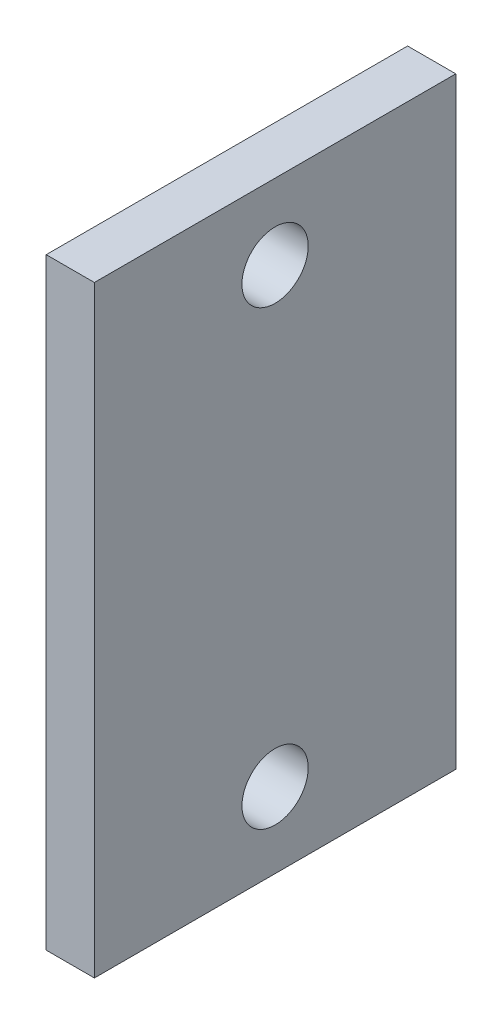
SolidWorks part; units mm, degrees
ref_plane "Front Plane" through (0, 0, 0) normal (0, 0, 1) x (1, 0, 0)
ref_plane "Top Plane" through (0, 0, 0) normal (0, 1, 0) x (1, 0, 0)
ref_plane "Right Plane" through (0, 0, 0) normal (1, 0, 0) x (0, 0, -1)
other "Configuration Table"
sketch "Sketch1" plane through (0, 0, 0) normal (1, 0, 0) x (0, 0, -1)
  line L1 (-6, -10) -> (6, -10)
  line L2 (-6, -10) -> (-6, 10)
  line L3 (-6, 10) -> (6, 10)
  line L4 (6, -10) -> (6, 10)
  line L5 (-6, -10) -> (6, 10) construction
  line L6 (-6, 10) -> (6, -10) construction
  point P6 (0, 0)
  dimension "D1" = 12
  dimension "D2" = 20
extrude "Board" add sketch "Sketch1" along normal blind 1.6
sketch "Sketch2" plane through (0, 0, 0) normal (1, 0, 0) x (0, 0, -1)
  line L0 (-1.4, -1.75) -> (1.4, -1.75)
  line L1 (1.4, -1.75) -> (1.4, 1.75)
  line L2 (1.4, 1.75) -> (-1.4, 1.75)
  line L3 (-1.4, 1.75) -> (-1.4, -1.75)
extrude "UV_Sensor" add sketch "Sketch2" against normal blind 1.2
sketch "Sketch3" plane through (0, 0, 0) normal (1, 0, 0) x (0, 0, -1)
  circle A0 centre (0, -7.5) radius 1.1
  circle A1 centre (0, 7.5) radius 1.1
  dimension "D1" = 2.2
  dimension "D2" = 2.2
extrude "Holes_M2" cut sketch "Sketch3" along normal through all and the other way through all
equation "\"Jar_OD\"= 90  'ASSUMED - Part G fallback - jar outer diameter"
equation "\"Jar_H\"= 120  'ASSUMED - Part G fallback - jar height"
equation "\"Pump_L\"= 45  'ASSUMED - Part G fallback"
equation "\"Pump_W\"= 24  'ASSUMED - Part G fallback"
equation "\"Pump_H\"= 33  'ASSUMED - Part G fallback"
equation "\"Pump_Outlet_OD\"= 7.5  'ASSUMED - Part G fallback"
equation "\"Tube_OD\"= 8  'ASSUMED - Part G fallback"
equation "\"Tube_ID\"= 6  'ASSUMED - Part G fallback"
equation "\"TDS_Body_Dia\"= 12  'ASSUMED - Part G fallback"
equation "\"TDS_Wet_Len\"= 45  'ASSUMED - Part G fallback - length in water"
equation "\"DS_Tube_Dia\"= 6  'ASSUMED - Part G fallback"
equation "\"DS_Tube_Len\"= 50  'ASSUMED - Part G fallback"
equation "\"ORP_Body_Dia\"= 12  'ASSUMED - Part G fallback"
equation "\"ORP_Body_Len\"= 150  'ASSUMED - Part G fallback"
equation "\"ORP_Cap_Dia\"= 16  'ASSUMED - Part G fallback"
equation "\"Turb_W\"= 33  'ASSUMED - Part G fallback - head width"
equation "\"Turb_D\"= 28  'ASSUMED - Part G fallback - head depth"
equation "\"Turb_H\"= 30  'ASSUMED - Part G fallback - head height"
equation "\"Turb_Slot_W\"= 10  'ASSUMED - Part G fallback - slot width"
equation "\"Flow_L\"= 62  'ASSUMED - Part G fallback YF-S201"
equation "\"Flow_W\"= 36  'ASSUMED - Part G fallback"
equation "\"Flow_H\"= 35  'ASSUMED - Part G fallback"
equation "\"Thread_G12_OD\"= 20.955  'ASSUMED - Part G fallback thread G1/2 (major diameter)"
equation "\"Valve_L\"= 75  'ASSUMED - Part G fallback"
equation "\"Valve_W\"= 45  'ASSUMED - Part G fallback"
equation "\"Valve_H\"= 60  'ASSUMED - Part G fallback"
equation "\"Tee_L\"= 40  'ASSUMED - Part G fallback - overall length"
equation "\"Tee_Branch_L\"= 25  'ASSUMED - Part G fallback"
equation "\"Tee_OD\"= 12  'ASSUMED - Part G fallback"
equation "\"Cuv_W\"= 12.5  'ASSUMED - old R3 cuvette (station suppressed in SS4)"
equation "\"Cuv_D\"= 12.5  'ASSUMED - old R3 cuvette (station suppressed in SS4)"
equation "\"Cuv_H\"= 45  'ASSUMED - old R3 cuvette (station suppressed in SS4)"
equation "\"LED_Board_L\"= 20  'ASSUMED - Part G fallback"
equation "\"LED_Board_W\"= 20  'ASSUMED - Part G fallback - LED at centre"
equation "\"GUVA_L\"= 20  'ASSUMED - Part G fallback"
equation "\"GUVA_W\"= 12  'ASSUMED - Part G fallback - sensor at centre"
equation "\"Reed_L\"= 27  'ASSUMED - Part G fallback MC-38 half"
equation "\"Reed_W\"= 14  'ASSUMED - Part G fallback"
equation "\"Reed_H\"= 8  'ASSUMED - Part G fallback"
equation "\"ESP_L\"= 51  'ASSUMED - Part G fallback"
equation "\"ESP_W\"= 28  'ASSUMED - Part G fallback"
equation "\"TFT_L\"= 58  'ASSUMED - Part G fallback - board"
equation "\"TFT_W\"= 35  'ASSUMED - Part G fallback - board"
equation "\"TFT_Win_L\"= 35  'ASSUMED - Part G fallback - visible window"
equation "\"TFT_Win_W\"= 28  'ASSUMED - Part G fallback - visible window"
equation "\"Relay_L\"= 50  'ASSUMED - Part G fallback"
equation "\"Relay_W\"= 26  'ASSUMED - Part G fallback"
equation "\"Relay_H\"= 19  'ASSUMED - Part G fallback"
equation "\"Mosfet_L\"= 34  'ASSUMED - Part G fallback"
equation "\"Mosfet_W\"= 17  'ASSUMED - Part G fallback"
equation "\"Mosfet_H\"= 12  'ASSUMED - Part G fallback"
equation "\"TDS_Board_L\"= 42  'ASSUMED - Part G fallback"
equation "\"TDS_Board_W\"= 32  'ASSUMED - Part G fallback"
equation "\"Turb_Board_L\"= 38  'ASSUMED - Part G fallback"
equation "\"Turb_Board_W\"= 28  'ASSUMED - Part G fallback"
equation "\"BNC_Thread_Dia\"= 9.5  'ASSUMED - Part G fallback"
equation "\"Plate_L\"= 420  'ASSUMED - Part G fallback"
equation "\"Plate_W\"= 297  'ASSUMED - Part G fallback"
equation "\"Plate_T\"= 6  'ASSUMED - Part G fallback"
equation "\"Probe_Clr\"= 0.3  'DESIGN VALUE - Part C rule 3 - printed probe hole = diameter + 0.3"
equation "\"Cuv_Clr\"= 0.2  'DESIGN VALUE - Part C rule 3 - cuvette pocket = size + 0.2"
equation "\"Label_H\"= 0.6  'DESIGN VALUE - Part D - raised label height"
equation "\"D1@Sketch1\" = \"GUVA_W\""
equation "\"D2@Sketch1\" = \"GUVA_L\""
equation "\"Booster_L\"= 150  'ASSUMED - Part G fallback - booster pump"
equation "\"Booster_W\"= 95  'ASSUMED - Part G fallback"
equation "\"Booster_H\"= 100  'ASSUMED - Part G fallback"
equation "\"PTube_OD\"= 6.35  'ASSUMED - Part G fallback - product tube 1/4 inch"
equation "\"Qz_Out\"= 12  'ASSUMED - Part G fallback - quartz channel outside square"
equation "\"Qz_Path\"= 10  'ASSUMED - Part G fallback - quartz channel inside light path"
equation "\"Qz_L\"= 40  'ASSUMED - Part G fallback - quartz channel length"
equation "\"LED860_Dia\"= 5  'ASSUMED - Part G fallback - 860 nm LED"
equation "\"BPW_L\"= 5.4  'ASSUMED - Part G fallback - BPW34"
equation "\"BPW_W\"= 4.3  'ASSUMED - Part G fallback - BPW34"
equation "\"Cart_Dia\"= 50  'ASSUMED - Part G fallback - sediment and pre-carbon cartridges"
equation "\"Cart_L\"= 255  'ASSUMED - Part G fallback"
equation "\"UF_Dia\"= 50  'ASSUMED - Part G fallback - UF cartridge"
equation "\"UF_L\"= 260  'ASSUMED - Part G fallback"
equation "\"RO_Dia\"= 62  'ASSUMED - Part G fallback - RO membrane housing"
equation "\"RO_L\"= 300  'ASSUMED - Part G fallback"
equation "\"UVC_Dia\"= 40  'ASSUMED - Part G fallback - UV-C chamber"
equation "\"UVC_L\"= 300  'ASSUMED - Part G fallback"
equation "\"Tank_W\"= 260  'ASSUMED - Part G fallback - storage tank"
equation "\"Tank_D\"= 160  'ASSUMED - Part G fallback"
equation "\"Tank_H\"= 300  'ASSUMED - Part G fallback"
equation "\"Cab_W\"= 400  'ASSUMED - Part G fallback - purifier cabinet"
equation "\"Cab_D\"= 270  'ASSUMED - Part G fallback"
equation "\"Cab_H\"= 560  'ASSUMED - Part G fallback"
equation "\"ORP_Board_L\"= 40  'ASSUMED - Part G fallback - ORP buffer board"
equation "\"ORP_Board_W\"= 30  'ASSUMED - Part G fallback"
equation "\"Opt_Board_L\"= 50  'ASSUMED - Part G fallback - optical front-end board"
equation "\"Opt_Board_W\"= 40  'ASSUMED - Part G fallback"
equation "\"Buck_L\"= 43  'ASSUMED - Part G fallback - 12 V to 5 V buck module"
equation "\"Buck_W\"= 21  'ASSUMED - Part G fallback"
equation "\"Buck_H\"= 14  'ASSUMED - Part G fallback"
equation "\"BB_L\"= 165  'ASSUMED - Part G fallback - breadboard (As_Built_R3 only)"
equation "\"BB_W\"= 55  'ASSUMED - Part G fallback"
equation "\"BB_H\"= 10  'ASSUMED - Part G fallback"
